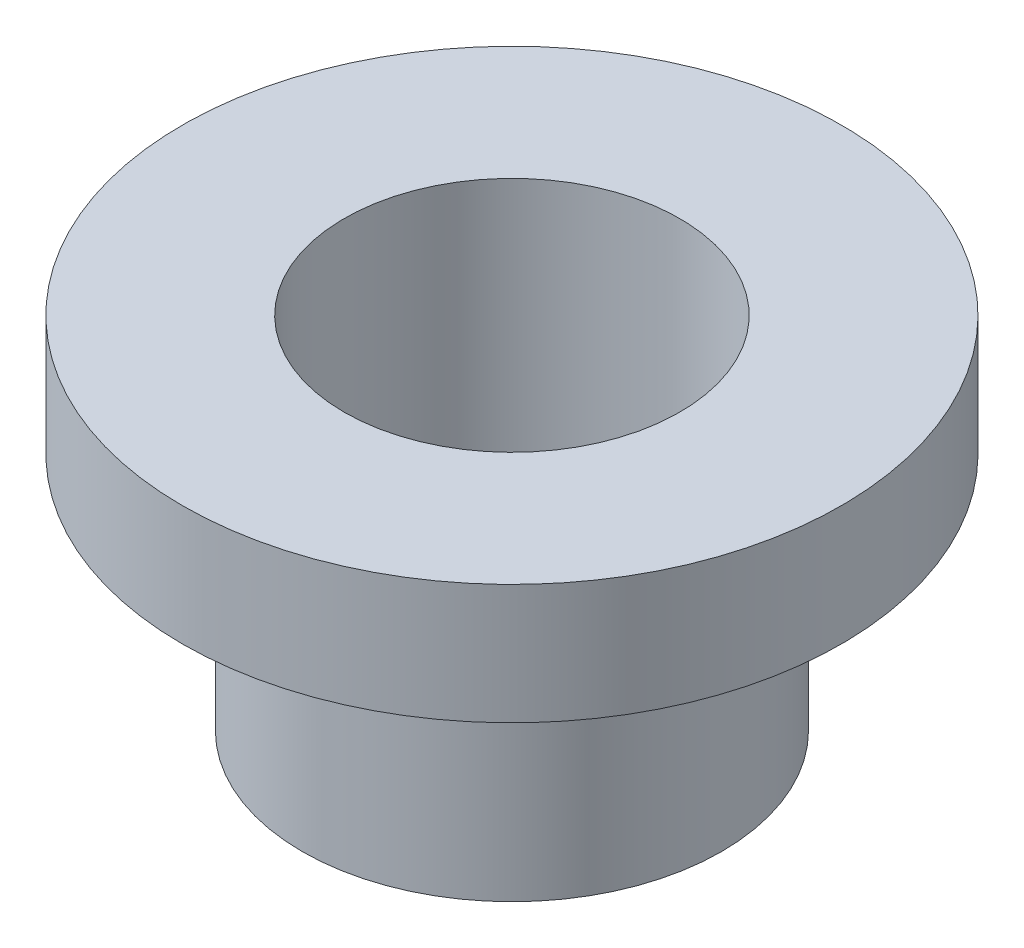
SolidWorks part; units mm, degrees
ref_plane "前视基准面" through (0, 0, 0) normal (0, 0, 1) x (1, 0, 0)
ref_plane "上视基准面" through (0, 0, 0) normal (0, 1, 0) x (1, 0, 0)
ref_plane "右视基准面" through (0, 0, 0) normal (1, 0, 0) x (0, 0, -1)
other "Configuration Table"
sketch "草图1" plane through (0, 0, 0) normal (0, 1, 0) x (1, 0, 0)
  circle A0 centre (0, 0) radius 1.4
  circle A1 centre (0, 0) radius 1.75
  dimension "D1" = 2.8
  dimension "D2" = 3.5
extrude "凸台-拉伸5" add sketch "草图1" along normal blind 3
sketch "草图6" plane through (0, 3, 0) normal (0, 1, 0) x (1, 0, 0)
  circle A0 centre (0, 0) radius 1.75
  circle A1 centre (0, 0) radius 2.75
  dimension "D1" = 1
extrude "凸台-拉伸6" add sketch "草图6" against normal blind 1
